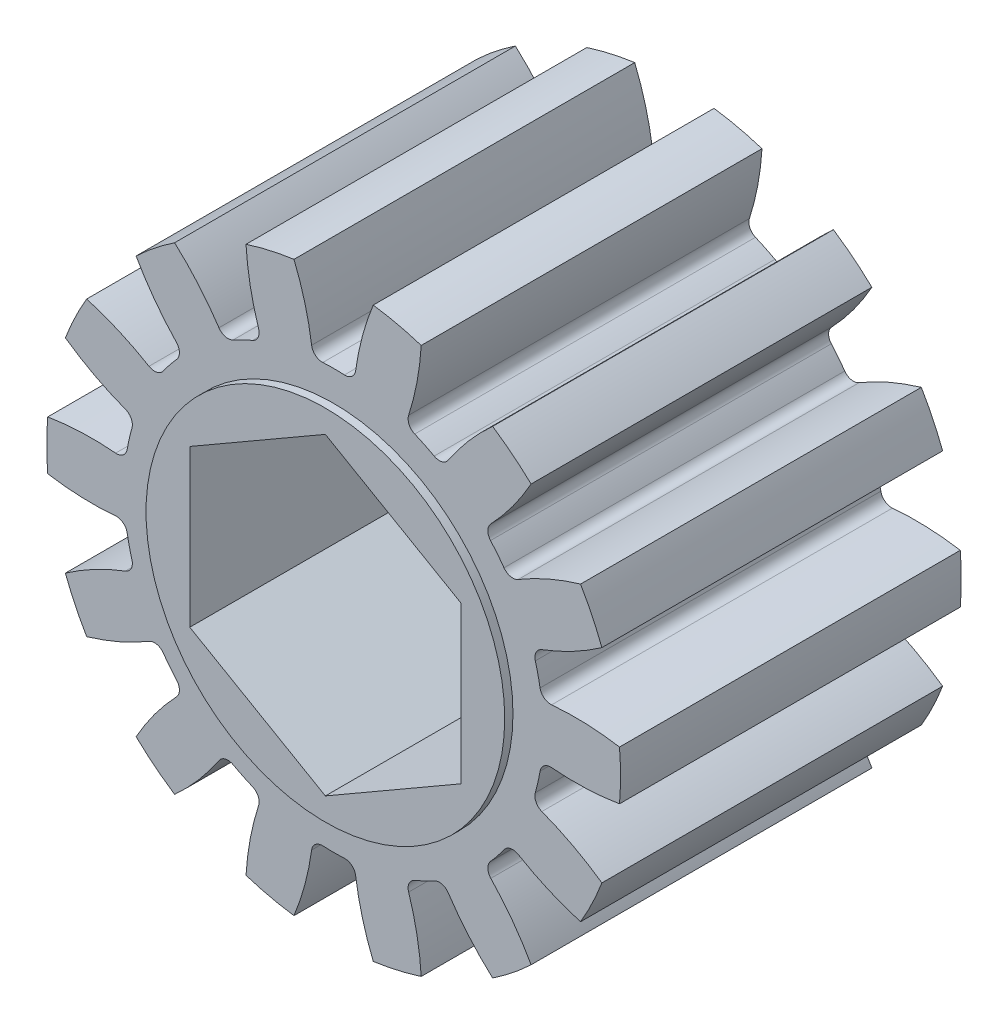
SolidWorks part; units mm, degrees
material "7075-T6 (SN)"
ref_plane "Alzado" through (0, 0, 0) normal (0, 0, 1) x (1, 0, 0)
ref_plane "Planta" through (0, 0, 0) normal (0, 1, 0) x (1, 0, 0)
ref_plane "Vista lateral" through (0, 0, 0) normal (1, 0, 0) x (0, 0, -1)
sketch "Croquis1" plane through (0, 0, 0) normal (0, 0, 1) x (1, 0, 0)
  circle A0 centre (0, 0) radius 8.89 construction
  circle A1 centre (0, 0) radius 10.16
  dimension "D" = 17.78
  dimension "OD" = 20.32
extrude "Saliente-Extruir1" add sketch "Croquis1" along normal mid plane 12.065
sketch "Croquis2" plane through (0, 0, 0) normal (0, 0, 1) x (1, 0, 0)
  line L0 (0, 0) -> (0, 10.16) construction
  line L1 (0, 0) -> (4.4083, 9.1538) construction
  line L2 (0, 0) -> (2.2608, 9.9053) construction
  line L3 (-0.737, 7.3839) -> (0, 0) construction
  line L4 (-0.9954, 8.8341) -> (0.9954, 8.8341) construction
  line L5 (0.9954, 8.8341) -> (2.9362, 8.3911) construction
  line L6 (-1.3161, 10.0744) -> (0, 4.9853) construction
  circle A0 centre (0, 0) radius 10.16 construction
  arc A2 (0.737, 7.3839) -> (-0.737, 7.3839) centre (0, 0) ccw
  circle A5 centre (0, 0) radius 8.89 construction
  arc A6 (-1.4032, 10.0626) -> (-0.737, 7.3839) centre (-10.2899, 6.4304) cw
  arc A7 (1.4032, 10.0626) -> (0.737, 7.3839) centre (10.2899, 6.4304) ccw
  arc A8 (1.4032, 10.0626) -> (-1.4032, 10.0626) centre (0, 0) ccw
  dimension "D1" = 25.714
  dimension "D2" = 12.857
  dimension "B" = 1.4694
  dimension "Pressure Angle" = 14.5
extrude "Cortar-Extruir1" cut sketch "Croquis2" against normal through all both and the other way through all
fillet "Redondeo1" radius 0.381 2 edges at (0.737, 7.3839, 0) (-0.737, 7.3839, 0)
pattern_circular "MatrizC1" count 14 over 360 about axis through (0, 0, 0) along (0, 0, 1) of "Cortar-Extruir1", "Redondeo1"
sketch "Croquis3" plane through (0, 0, 0) normal (0, 0, 1) x (1, 0, 0)
  circle A0 centre (0, 0) radius 6.35
  dimension "sp" = 12.7
extrude "Saliente-Extruir2" add sketch "Croquis3" along normal mid plane 12.6492
sketch "Croquis4" plane through (0, 0, 0) normal (0, 0, 1) x (1, 0, 0)
  line L1 (0, 5.5433) -> (-4.8006, 2.7716)
  line L2 (-4.8006, 2.7716) -> (-4.8006, -2.7716)
  line L3 (-4.8006, -2.7716) -> (0, -5.5433)
  line L4 (0, -5.5433) -> (4.8006, -2.7716)
  line L5 (4.8006, -2.7716) -> (4.8006, 2.7716)
  line L6 (4.8006, 2.7716) -> (0, 5.5433)
  circle A0 centre (0, 0) radius 4.8006 construction
  dimension "D1" = 9.6012
extrude "Cortar-Extruir2" cut sketch "Croquis4" against normal through all both and the other way through all
equation "\"Number of teeth\"=14"
equation "\"Diametral Pitch\"= 20"
equation "\"Pressure Angle\"= 14.5"
equation "\"D@Croquis1\"=\"Number of teeth\"/\"Diametral Pitch\""
equation "\"OD@Croquis1\"=(\"Number of teeth\"+2) /\"Diametral Pitch\""
equation "\"D2@Croquis2\"=(360 / \"Number of teeth\")/ 2."
equation "\"D1@Croquis2\"=360 / \"Number of teeth\""
equation "\"B@Croquis2\"=1.157 / \"Diametral Pitch\""
equation "\"Pressure Angle@Croquis2\" = \"Pressure Angle\""
equation "\"D1@Redondeo1\"=(pi / \"Diametral Pitch\") * .0955"
equation "\"D1@MatrizC1\"=\"Number of teeth\""
equation "\"Tt@Saliente-Extruir1\"=if( \"Number of teeth\"=>30,0.375,0.475)"
